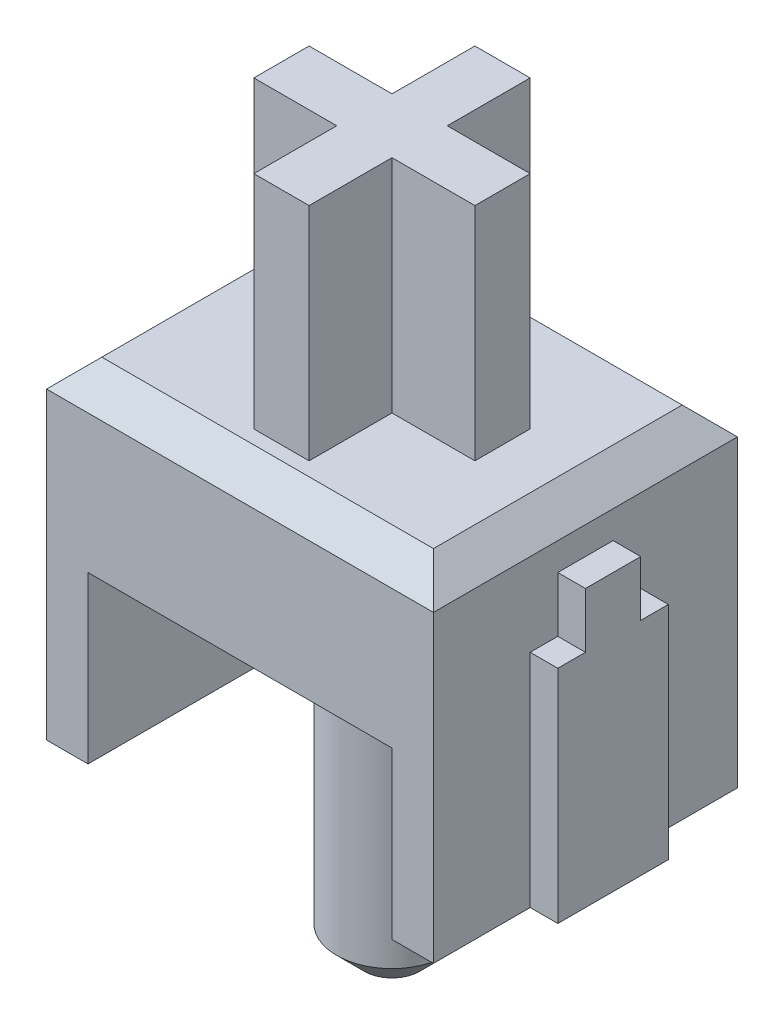
SolidWorks part; units mm, degrees
ref_plane "Plan de face" through (0, 0, 0) normal (0, 0, 1) x (1, 0, 0)
ref_plane "Plan de dessus" through (0, 0, 0) normal (0, 1, 0) x (1, 0, 0)
ref_plane "Plan de droite" through (0, 0, 0) normal (1, 0, 0) x (0, 0, -1)
sketch "Esquisse1" plane through (0, 0, 0) normal (0, 1, 0) x (1, 0, 0)
  line L1 (-3.5, 2.75) -> (3.5, 2.75)
  line L2 (-3.5, 2.75) -> (-3.5, -2.75)
  line L3 (-3.5, -2.75) -> (3.5, -2.75)
  line L4 (3.5, 2.75) -> (3.5, -2.75)
  line L5 (-3.5, 2.75) -> (3.5, -2.75) construction
  line L6 (-3.5, -2.75) -> (3.5, 2.75) construction
  point P0 (0, 0)
  dimension "D1" = 5.5
  dimension "D2" = 7
extrude "Boss.-Extru.1" add sketch "Esquisse1" along normal blind 6
sketch "Esquisse2" plane through (0, 0, 0) normal (0, -1, 0) x (1, 0, 0)
  line L0 (3.5, -2.75) -> (-3.5, -2.75) construction
  line L1 (-2.75, 2.75) -> (2.75, 2.75)
  line L2 (-2.75, 2.75) -> (-2.75, -2.75)
  line L3 (-2.75, -2.75) -> (2.75, -2.75)
  line L4 (2.75, 2.75) -> (2.75, -2.75)
  line L5 (-2.75, 2.75) -> (2.75, -2.75) construction
  line L6 (-2.75, -2.75) -> (2.75, 2.75) construction
  point P1 (0, 0)
  dimension "D1" = 5.5
  dimension "D2" = 5.5
sketch "Esquisse3" plane through (-3.5, 0, 0) normal (-1, 0, 0) x (0, 0, 1)
  line L0 (0, 0) -> (-1, 0)
  line L1 (2.75, 0) -> (-2.75, 0) construction
  line L2 (-1, 0) -> (-1, 4)
  line L3 (-1, 4) -> (-0.5, 4)
  line L4 (-0.5, 4) -> (-0.5, 5)
  line L5 (-0.5, 5) -> (0.5, 5)
  line L6 (0.5, 5) -> (0.5, 4)
  line L7 (0.5, 4) -> (1, 4)
  line L8 (1, 4) -> (1, 0)
  line L9 (-2.75, 0) -> (2.75, 0) construction
  line L10 (1, 0) -> (0, 0)
  dimension "D1" = 0.5
  dimension "D2" = 0.5
  dimension "D3" = 1
  dimension "D4" = 4
  dimension "D5" = 1
  dimension "D6" = 1
  dimension "D7" = 4
  dimension "D8" = 1
  dimension "D9" = 1
extrude "Boss.-Extru.2" add sketch "Esquisse3" along normal blind 0.5 and the other way blind 7.5
extrude "Enlèv. mat.-Extru.2" cut sketch "Esquisse2" against normal blind 3
sketch "Esquisse4" plane through (0, 6, 0) normal (0, 1, 0) x (1, 0, 0)
  line L1 (-2, 0.5) -> (2, 0.5)
  line L2 (-2, 0.5) -> (-2, -0.5)
  line L3 (-2, -0.5) -> (2, -0.5)
  line L4 (2, 0.5) -> (2, -0.5)
  line L5 (-2, 0.5) -> (2, -0.5) construction
  line L6 (-2, -0.5) -> (2, 0.5) construction
  line L7 (-0.5, -2) -> (0.5, -2)
  line L8 (-0.5, -2) -> (-0.5, 2)
  line L9 (-0.5, 2) -> (0.5, 2)
  line L10 (0.5, -2) -> (0.5, 2)
  line L11 (-0.5, -2) -> (0.5, 2) construction
  line L12 (-0.5, 2) -> (0.5, -2) construction
  point P0 (0, 0)
  point P6 (0, 0)
  dimension "D1" = 1
  dimension "D2" = 1
  dimension "D3" = 4
  dimension "D4" = 4
extrude "Boss.-Extru.3" add sketch "Esquisse4" along normal blind 4 contours L10 L3 L4 L1 | L7 L10 L3 L8 | L3 L8 L1 L2 | L3 L10 L1 L8 | L1 L10 L9 L8
sketch "Esquisse5" plane through (0, 3, 0) normal (0, -1, 0) x (1, 0, 0)
  circle A0 centre (0, 0) radius 2
  dimension "D1" = 4
extrude "Enlèv. mat.-Extru.3" cut sketch "Esquisse5" against normal blind 2
sketch "Esquisse6" plane through (0, 5, 0) normal (0, -1, 0) x (1, 0, 0)
  circle A0 centre (0, 0) radius 1
  dimension "D1" = 2
extrude "Boss.-Extru.4" add sketch "Esquisse6" along normal blind 8
chamfer "Chanfrein1" distance 0.5 angle 45 5 edges at (0, -3, -1) (0, 6, -2.75) (-3.5, 6, 0) (0, 6, 2.75) (3.5, 6, 0)
